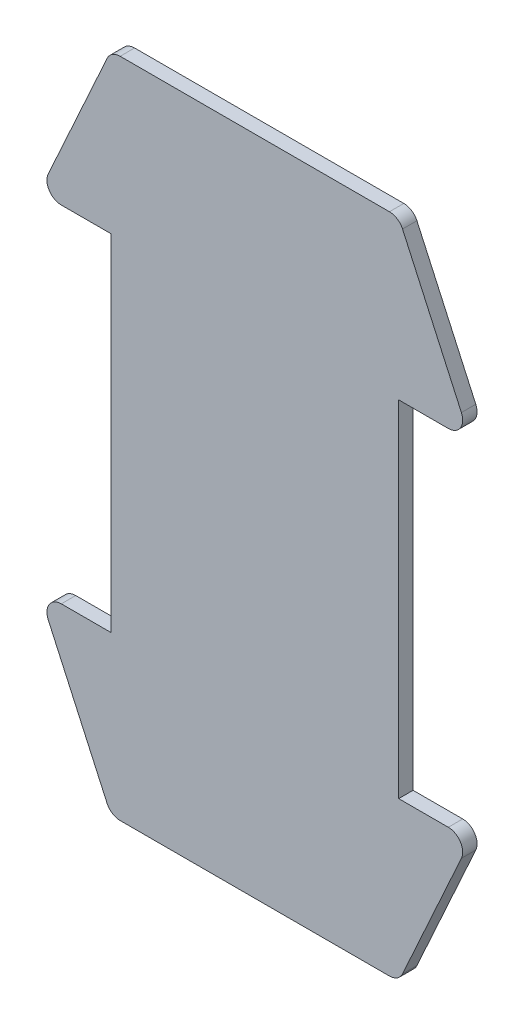
SolidWorks part; units mm, degrees
ref_plane "Front Plane" through (0, 0, 0) normal (0, 0, 1) x (1, 0, 0)
ref_plane "Top Plane" through (0, 0, 0) normal (0, 1, 0) x (1, 0, 0)
ref_plane "Right Plane" through (0, 0, 0) normal (1, 0, 0) x (0, 0, -1)
sketch "Sketch3" plane through (0, 0, 0) normal (0, 0, 1) x (1, 0, 0)
  line L0 (0, 50.499) -> (0, -57.5351) construction
  line L1 (50, 115) -> (-50, 115)
  line L2 (-50, 115) -> (-75, 60)
  line L3 (-75, 60) -> (-50, 60)
  line L4 (-50, 60) -> (-50, -60)
  line L5 (-94.2851, 0) -> (80.5838, 0) construction
  line L6 (0, -50.499) -> (0, 57.5351) construction
  line L7 (-75, -60) -> (-50, -60)
  line L8 (-50, -115) -> (-75, -60)
  line L9 (50, -115) -> (-50, -115)
  line L10 (50, -115) -> (75, -60)
  line L11 (75, -60) -> (50, -60)
  line L12 (50, 60) -> (50, -60)
  line L13 (75, 60) -> (50, 60)
  line L14 (50, 115) -> (75, 60)
  point P3 (50, 0)
  point P13 (-50, 0)
  point P17 (0, -115)
  point P22 (0, 115)
  dimension "D1" = 50
  dimension "D2" = 25
  dimension "D3" = 75
  dimension "D4" = 115
  dimension "D5" = 60
extrude "Boss-Extrude1" add sketch "Sketch3" against normal blind 5
fillet "Fillet2" radius 5 8 edges at (-50, -115, -2.5) (-75, -60, -2.5) (50, -115, -2.5) (75, -60, -2.5) (75, 60, -2.5) (-75, 60, -2.5) (50, 115, -2.5) (-50, 115, -2.5)
